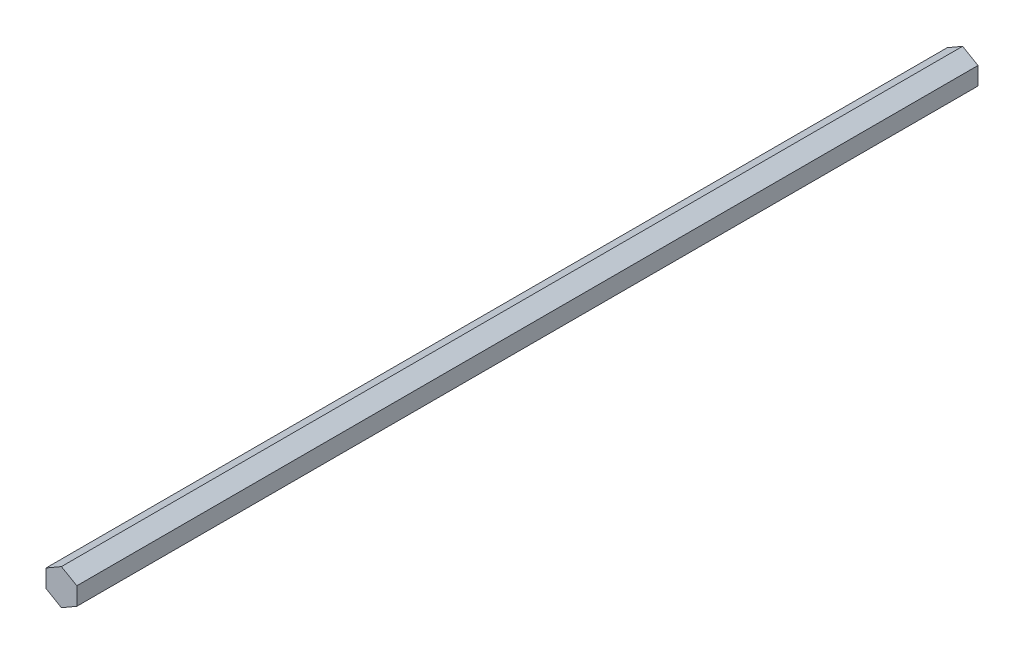
SolidWorks part; units mm, degrees
ref_plane "Front Plane" through (0, 0, 0) normal (0, 0, 1) x (1, 0, 0)
ref_plane "Top Plane" through (0, 0, 0) normal (0, 1, 0) x (1, 0, 0)
ref_plane "Right Plane" through (0, 0, 0) normal (1, 0, 0) x (0, 0, -1)
sketch "Sketch1" plane through (0, 0, 0) normal (0, 0, 1) x (1, 0, 0)
  line L1 (0, 7.3323) -> (-6.35, 3.6662) construction
  line L2 (-6.35, 3.6662) -> (-6.35, -3.6662) construction
  line L3 (-6.35, -3.6662) -> (0, -7.3323) construction
  line L4 (0, -7.3323) -> (6.35, -3.6662) construction
  line L5 (6.35, -3.6662) -> (6.35, 3.6662) construction
  line L6 (6.35, 3.6662) -> (0, 7.3323) construction
  circle A2 centre (0, 0) radius 6.35 construction
  dimension "Width" = 12.7
sketch "Sketch2" plane through (0, 0, 0) normal (1, 0, 0) x (0, 0, -1)
  line L0 (-152.4, 7.3323) -> (152.4, 7.3323) construction
  point P2 (0, 7.3323)
  point P3 (120.65, 7.3323)
  point P4 (-120.65, 7.3323)
  dimension "Length" = 304.8
  dimension "D2" = 31.75
  dimension "D1" = 31.75
sketch "Sketch3" plane through (0, 0, 0) normal (0, 0, 1) x (1, 0, 0)
  line L0 (-6.35, -3.6662) -> (0, -7.3323) construction
  line L1 (0, -7.3323) -> (6.35, -3.6662) construction
  line L2 (6.35, -3.6662) -> (6.35, 3.6662) construction
  line L3 (6.35, 3.6662) -> (0, 7.3323) construction
  line L4 (0, 7.3323) -> (-6.35, 3.6662) construction
  line L5 (-6.35, 3.6662) -> (-6.35, -3.6662) construction
  line L6 (-6.35, -3.6662) -> (0, -7.3323)
  line L7 (0, -7.3323) -> (6.35, -3.6662)
  line L8 (6.35, -3.6662) -> (6.35, 3.6662)
  line L9 (6.35, 3.6662) -> (0, 7.3323)
  line L10 (0, 7.3323) -> (-6.35, 3.6662)
  line L11 (-6.35, 3.6662) -> (-6.35, -3.6662)
extrude "Boss-Extrude2" add sketch "Sketch3" along normal up to vertex (152.4 mm away) and the other way up to vertex (152.4 mm away) up to point (0, 7.3323, 152.4) other way up to point (0, 7.3323, -152.4)
sketch "Sketch4" plane through (0, 0, 152.4) normal (0, 0, 1) x (1, 0, 0)
  line L6 (-6.35, 3.6662) -> (-6.35, -3.6662)
  line L7 (-6.35, -3.6662) -> (0, -7.3323)
  line L8 (0, -7.3323) -> (6.35, -3.6662)
  line L9 (6.35, -3.6662) -> (6.35, 3.6662)
  line L10 (6.35, 3.6662) -> (0, 7.3323)
  line L11 (0, 7.3323) -> (-6.35, 3.6662)
  line L12 (-6.35, 3.6662) -> (-6.35, -3.6662)
  line L13 (-6.35, -3.6662) -> (0, -7.3323)
  line L14 (0, -7.3323) -> (6.35, -3.6662)
  line L15 (6.35, -3.6662) -> (6.35, 3.6662)
  line L16 (6.35, 3.6662) -> (0, 7.3323)
  line L17 (0, 7.3323) -> (-6.35, 3.6662)
  dimension "D1" = 0
extrude "Boss-Extrude3" add sketch "Sketch4" along normal blind 66.548
equation "\"D2@Sketch2\" = \"D1@Sketch2\""
equation "\"D1@Sketch2\" = \"Width@Sketch1\" * 2.5"
